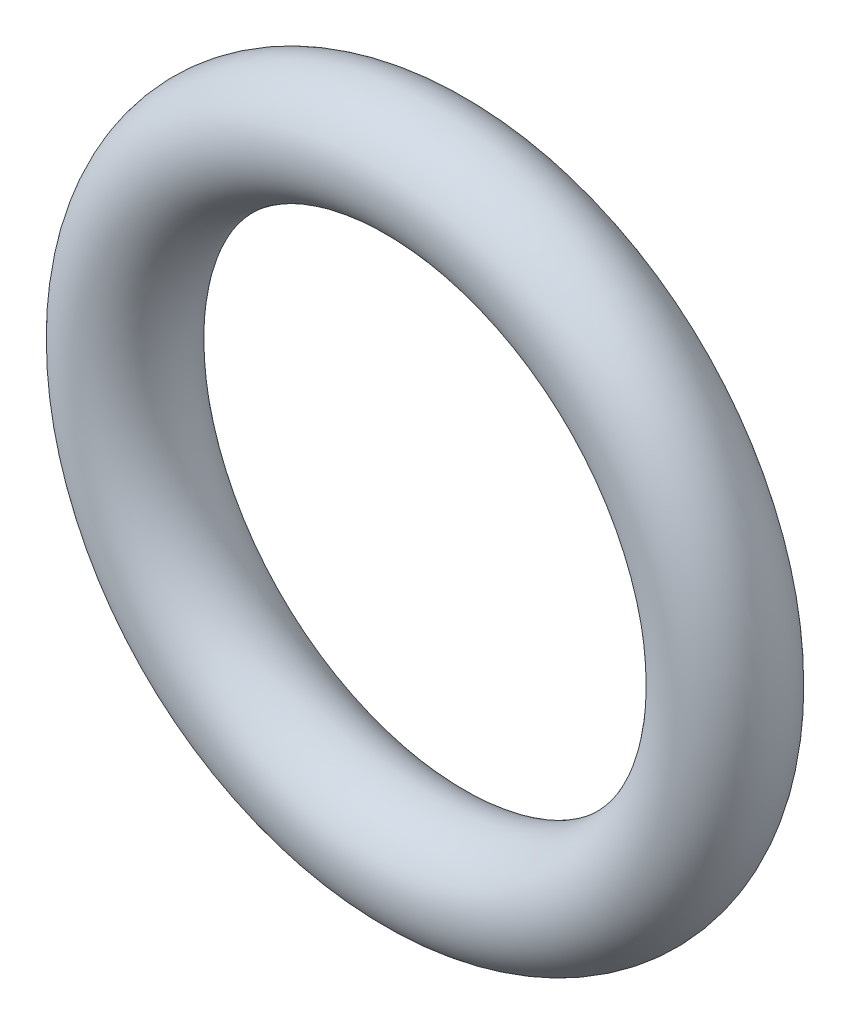
SolidWorks part; units mm, degrees
ref_plane "Front" through (0, 0, 0) normal (0, 0, 1) x (1, 0, 0)
ref_plane "Top" through (0, 0, 0) normal (0, 1, 0) x (1, 0, 0)
ref_plane "Right" through (0, 0, 0) normal (1, 0, 0) x (0, 0, -1)
sketch "Sketch1" plane through (0, 0, 0) normal (1, 0, 0) x (0, -1, 0)
  line L0 (0, -1.7653) -> (0, 1.7653) construction
  line L2 (-12.3914, 0) -> (12.3914, 0) construction
  line L3 (-7.7343, 0) -> (7.7343, 0) construction
  circle A0 centre (9.4996, 0) radius 1.7653
  point P9 (7.7343, 0)
  point P10 (11.2649, 0)
  point P13 (9.4996, 1.7653)
  point P14 (9.4996, -1.7653)
  dimension "Width" = 3.5306
  dimension "ID" = 15.4686
revolve "Revolve1" add sketch "Sketch1" angle 360 about L0
